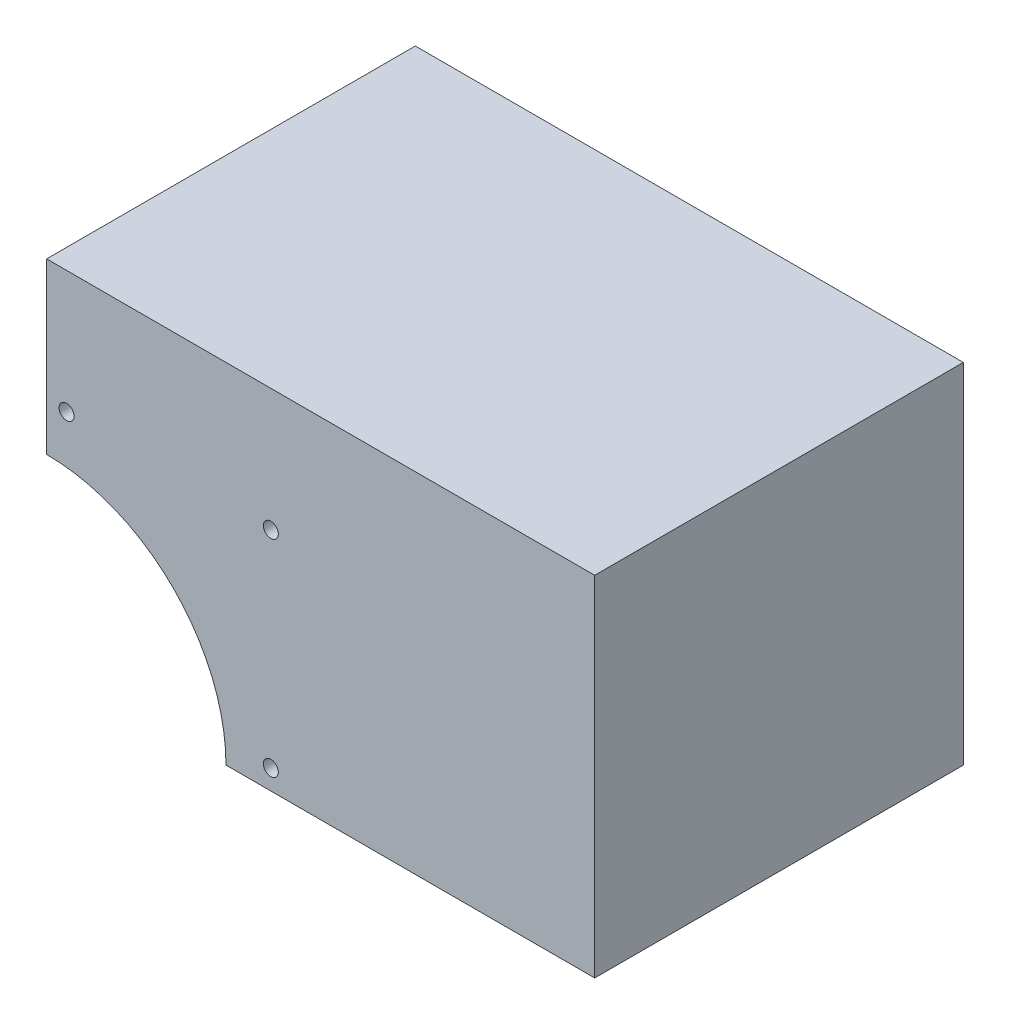
SolidWorks part; units mm, degrees
ref_plane "前视基准面" through (0, 0, 0) normal (0, 0, 1) x (1, 0, 0)
ref_plane "上视基准面" through (0, 0, 0) normal (0, 1, 0) x (1, 0, 0)
ref_plane "右视基准面" through (0, 0, 0) normal (1, 0, 0) x (0, 0, -1)
other "Configuration Table"
sketch "草图1" plane through (0, 0, 0) normal (0, 0, 1) x (1, 0, 0)
  line L1 (0, 0) -> (55, 0)
  line L2 (0, 0) -> (0, 35)
  line L3 (0, 35) -> (55, 35)
  line L4 (55, 0) -> (55, 35)
  dimension "D1" = 55
  dimension "D2" = 35
extrude "凸台-拉伸1" add sketch "草图1" along normal blind 37
sketch "草图3" plane through (0, 0, 0) normal (0, -1, 0) x (1, 0, 0)
  line L0 (27.5, 37) -> (27.5, -49963) construction
  line L1 (0, 37) -> (55, 37) construction
  line L7 (0, 18.5) -> (50000, 18.5) construction
  line L8 (0, 37) -> (0, 0) construction
  line L10 (0, 34.5) -> (26, 34.5)
  line L11 (0, 34.5) -> (0, 2.5)
  line L12 (0, 2.5) -> (26, 2.5)
  line L13 (26, 34.5) -> (26, 2.5)
  point P4 (27.5, 37)
  point P9 (0, 18.5)
  point P14 (0, 18.5)
  dimension "D1" = 26
  dimension "D2" = 32
extrude "切除-拉伸1" cut sketch "草图3" against normal offset from surface (32 mm away) 3 up to face at (27.5, 35, 18.5)
sketch "草图4" plane through (0, 0, 37) normal (0, 0, 1) x (1, 0, 0)
  line L0 (27.5, 35) -> (27.5, -49965) construction
  line L1 (55, 35) -> (0, 35) construction
  line L2 (0, 0) -> (55, 0) construction
  line L3 (2, 22.7) -> (22.5, 22.7) construction
  line L4 (2, 22.7) -> (2, 2) construction
  line L5 (2, 2) -> (22.5, 2) construction
  line L6 (22.5, 22.7) -> (22.5, 2) construction
  line L7 (0, 35) -> (0, 0) construction
  circle A0 centre (2, 2) radius 0.75
  circle A1 centre (22.5, 2) radius 0.75
  circle A2 centre (22.5, 22.7) radius 0.75
  circle A3 centre (2, 22.7) radius 0.75
  point P4 (27.5, 35)
  dimension "D5" = 1.5
  dimension "D6" = 1.5
  dimension "D7" = 1.5
  dimension "D8" = 1.5
  dimension "D1" = 2
  dimension "D2" = 2
  dimension "D3" = 20.7
  dimension "D4" = 20.5
extrude "切除-拉伸2" cut sketch "草图4" against normal up to next
sketch "草图5" plane through (0, 0, 0) normal (0, 0, -1) x (-1, 0, 0)
  line L1 (-2, 2) -> (-22.5, 2) construction
  line L2 (-2, 2) -> (-2, 26.45) construction
  line L3 (-2, 26.45) -> (-22.5, 26.45) construction
  line L4 (-22.5, 2) -> (-22.5, 26.45) construction
  circle A0 centre (-22.5, 2) radius 0.75 construction
  circle A1 centre (-2, 2) radius 0.75 construction
  circle A2 centre (-22.5, 2) radius 0.75
  circle A3 centre (-2, 2) radius 0.75
  circle A4 centre (-2, 26.45) radius 0.75
  circle A5 centre (-22.5, 26.45) radius 0.75
  dimension "D2" = 1.5
  dimension "D3" = 1.5
  dimension "D1" = 24.45
extrude "切除-拉伸3" cut sketch "草图5" against normal up to next
sketch "草图6" plane through (0, 0, 0) normal (0, -1, 0) x (1, 0, 0)
  line L0 (23.25, 37) -> (21.75, 37) construction
  line L1 (2.75, 37) -> (1.25, 37) construction
  line L2 (23.25, 37) -> (21.75, 37)
  line L3 (2.75, 37) -> (1.25, 37)
  line L4 (2, 37) -> (22.5, 37) construction
  line L5 (12.25, 37) -> (12.25, -49963) construction
  line L6 (26, 34.5) -> (0, 34.5) construction
  line L7 (3.75, 36) -> (20.75, 36)
  line L8 (3.75, 36) -> (3.75, 34.5)
  line L9 (3.75, 34.5) -> (20.75, 34.5)
  line L10 (20.75, 36) -> (20.75, 34.5)
  point P8 (12.25, 37)
  point P13 (12.25, 34.5)
  line M8 (0, 34.5) -> (26, 34.5)
  dimension "D1" = 1.5
  dimension "D2" = 17
extrude "切除-拉伸4" cut sketch "草图6" against normal blind 27 contours L10 L7 L8 M8
sketch "草图7" plane through (0, 0, 37) normal (0, 0, 1) x (1, 0, 0)
  circle A0 centre (0, 0) radius 18
  dimension "D1" = 36
extrude "切除-拉伸5" cut sketch "草图7" against normal through all
